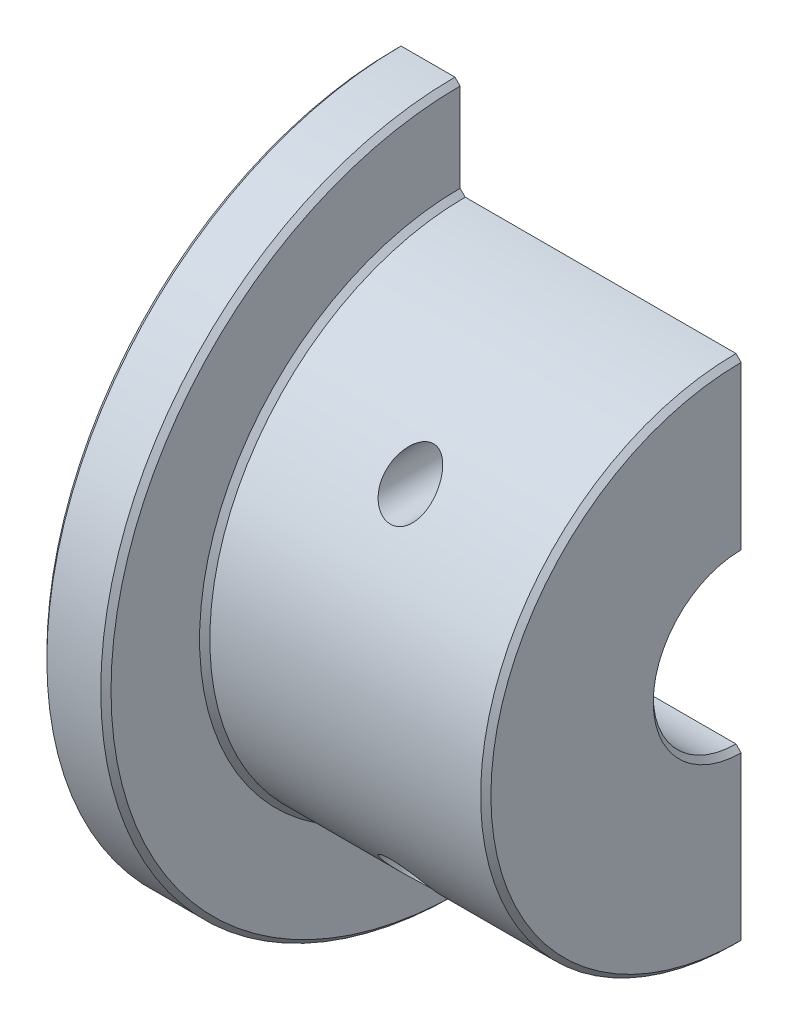
SolidWorks part; units mm, degrees
ref_plane "Front Plane" through (0, 0, 0) normal (0, 0, 1) x (1, 0, 0)
ref_plane "Top Plane" through (0, 0, 0) normal (0, 1, 0) x (1, 0, 0)
ref_plane "Right Plane" through (0, 0, 0) normal (1, 0, 0) x (0, 0, -1)
sketch "Sketch1" plane through (0, 0, 0) normal (1, 0, 0) x (0, 0, -1)
  circle A0 centre (0, 0) radius 12.6365
extrude "Boss-Extrude1" add sketch "Sketch1" along normal blind 21.844 contours A0
ref_plane "Plane1" through (7.9375, 0, 0) normal (1, 0, 0) x (0, 0, -1)
sketch "Sketch2" plane through (7.9375, 0, 0) normal (1, 0, 0) x (0, 0, -1)
  circle A0 centre (0, 0) radius 17.526
extrude "Boss-Extrude2" add sketch "Sketch2" against normal blind 3.175
chamfer "Chamfer1" distance 0.254 angle 45 6 edges at (21.844, 0, -12.6365) (0, 0, -12.6365) (7.9375, 0, -12.6365) (4.7625, 0, -12.6365) (4.7625, 0, -17.526) (7.9375, 0, -17.526)
sketch "Sketch3" plane through (21.844, 0, 0) normal (1, 0, 0) x (0, 0, -1)
  circle A0 centre (0, 0) radius 4.0957
extrude "Cut-Extrude1" cut sketch "Sketch3" against normal through all
chamfer "Chamfer2" distance 0.254 angle 45 2 edges at (0, 0, -4.0957) (21.844, 0, -4.0957)
sketch "Sketch4" plane through (0, 0, 0) normal (0, 0, 1) x (1, 0, 0)
  circle A0 centre (14.8908, 0) radius 1.9844
extrude "Cut-Extrude2" cut sketch "Sketch4" against normal blind 22.606
sketch "Sketch5" plane through (0, 0, 0) normal (-1, 0, 0) x (0, 0, 1)
  circle A0 centre (0, 0) radius 12.8905
extrude "Cut-Extrude3" cut sketch "Sketch5" against normal blind 4.7625
sketch "Sketch6" plane through (0, 0, 0) normal (0, 0, 1) x (1, 0, 0)
  line L1 (27.0904, -19.5047) -> (0.8921, -19.5047)
  line L2 (27.0904, -19.5047) -> (27.0904, 19.5047)
  line L3 (27.0904, 19.5047) -> (0.8921, 19.5047)
  line L4 (0.8921, -19.5047) -> (0.8921, 19.5047)
  line L5 (27.0904, -19.5047) -> (0.8921, 19.5047) construction
  line L6 (27.0904, 19.5047) -> (0.8921, -19.5047) construction
  point P0 (13.9912, 0)
extrude "Cut-Extrude4" cut sketch "Sketch6" against normal blind 41.783
sketch "Sketch7" plane through (0, 0, 0) normal (0, 0, -1) x (-1, 0, 0)
  circle A2 centre (-14.8908, 8.3661) radius 1.1906
extrude "Cut-Extrude5" cut sketch "Sketch7" against normal blind 12.7
mirror "Mirror1" about plane through (0, 0, 0) normal (0, 1, 0) of "Cut-Extrude5"
sketch "Sketch8" plane through (4.7625, 0, 0) normal (-1, 0, 0) x (0, 0, 1)
  line L0 (0, -10.16) -> (0, -6.604)
  line L1 (0, 10.16) -> (0, 6.604)
  arc A0 (0, -6.604) -> (0, 6.604) centre (0, 0) ccw
  arc A1 (0, -10.16) -> (0, 10.16) centre (0, 0) ccw
extrude "Boss-Extrude3" add sketch "Sketch8" along normal blind 1.524
